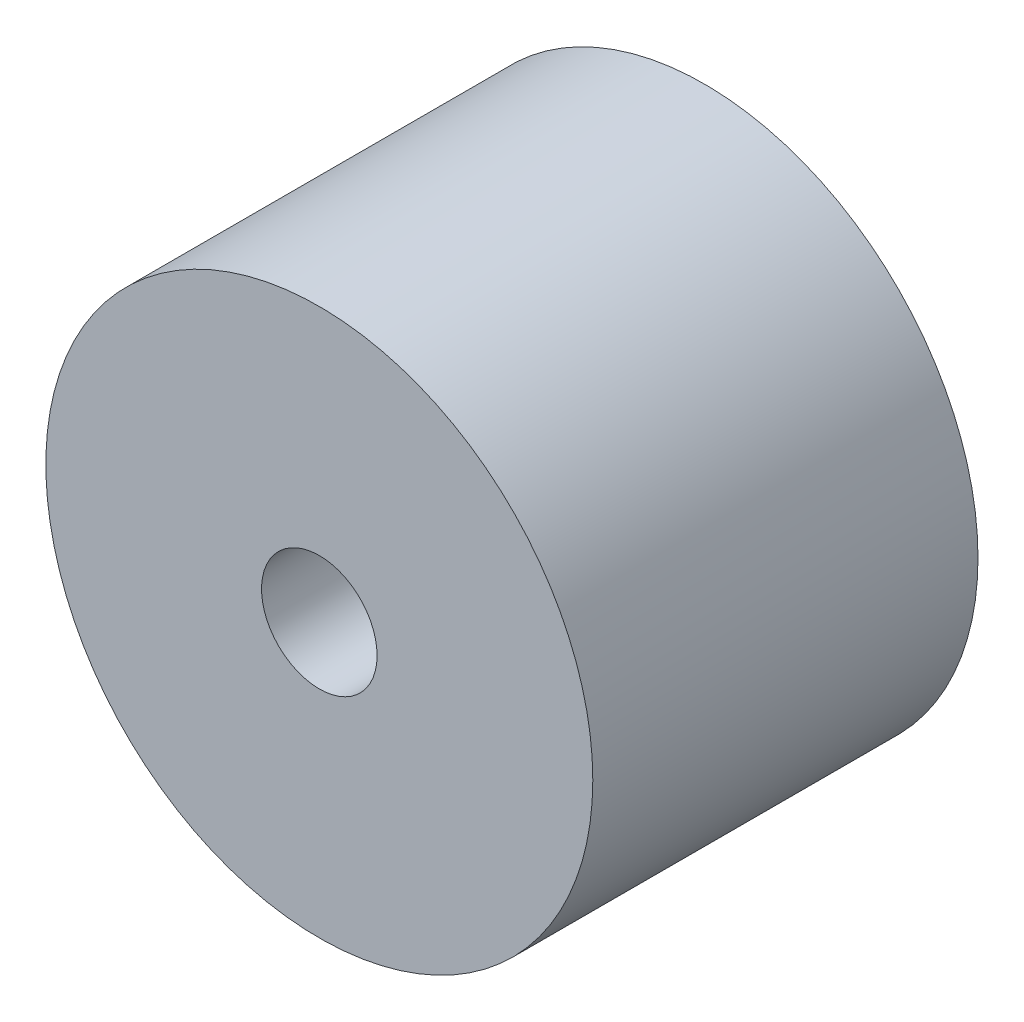
SolidWorks part; units mm, degrees
ref_plane "Front Plane" through (0, 0, 0) normal (0, 0, 1) x (1, 0, 0)
ref_plane "Top Plane" through (0, 0, 0) normal (0, 1, 0) x (1, 0, 0)
ref_plane "Right Plane" through (0, 0, 0) normal (1, 0, 0) x (0, 0, -1)
sketch "Sketch1" plane through (0, 0, 0) normal (0, 0, 1) x (1, 0, 0)
  circle A0 centre (0, 0) radius 14.2
  circle A1 centre (0, 0) radius 3
extrude "Connection_space_only_NO_THREADS_OR_SEALS" add sketch "Sketch1" along normal blind 20
